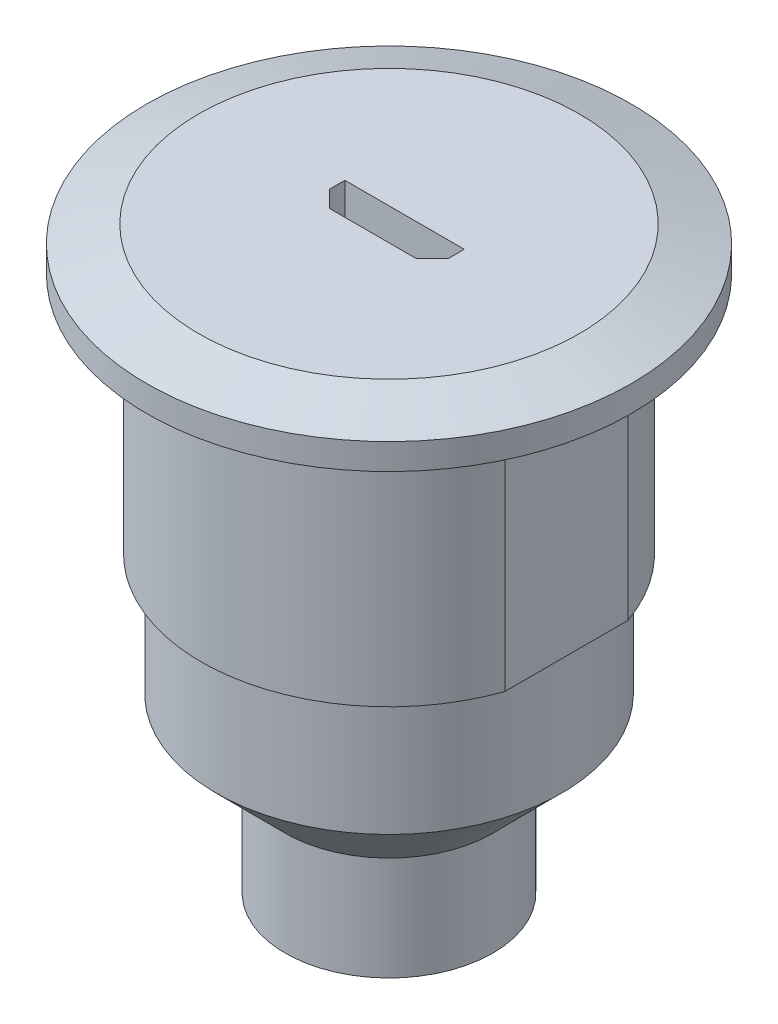
SolidWorks part; units mm, degrees
ref_plane "Plan de face" through (0, 0, 0) normal (0, 0, 1) x (1, 0, 0)
ref_plane "Plan de dessus" through (0, 0, 0) normal (0, 1, 0) x (1, 0, 0)
ref_plane "Plan de droite" through (0, 0, 0) normal (1, 0, 0) x (0, 0, -1)
sketch "Esquisse1" plane through (0, 0, 0) normal (0, 0, 1) x (1, 0, 0)
  line L0 (0, 33.5) -> (0, -37.1703) construction
  line L1 (0, 33.5) -> (-11, 33.5)
  line L2 (-11, 33.5) -> (-14, 32.5)
  line L3 (-14, 32.5) -> (-14, 31)
  line L4 (-14, 31) -> (-10.85, 31)
  line L5 (-10.85, 31) -> (-10.85, 17)
  line L6 (-10.85, 17) -> (-9.985, 17)
  line L7 (-9.985, 17) -> (-9.985, 10)
  line L8 (-9.985, 10) -> (-6, 6)
  line L9 (-6, 6) -> (-6, 0)
  line L10 (-6, 0) -> (0, 0)
  line L11 (0, 33.5) -> (0, 0)
  dimension "D1" = 11
  dimension "D2" = 14
  dimension "D3" = 2.5
  dimension "D4" = 1.5
  dimension "D5" = 14
  dimension "D6" = 7
  dimension "D7" = 31
  dimension "D8" = 6
  dimension "D9" = 6
  dimension "D10" = 10.85
  dimension "D11" = 9.985
revolve "Révolution1" add sketch "Esquisse1" angle 360 about L0
sketch "Esquisse2" plane through (0, 33.5, 0) normal (0, 1, 0) x (1, 0, 0)
  line L0 (-3.45, 0.9) -> (3.45, 0.9)
  line L1 (3.45, 0.9) -> (3.45, 0)
  line L2 (3.45, 0) -> (2.5, -0.95)
  line L3 (2.5, -0.95) -> (-2.5, -0.95)
  line L4 (-2.5, -0.95) -> (-3.45, 0)
  line L5 (-3.45, 0) -> (-3.45, 0.9)
  line L6 (-3.45, 0) -> (-3.45, -0.95) construction
  circle A0 centre (0, 0) radius 11 construction
  circle A1 centre (0, 0) radius 11 construction
  point P3 (0, 0.9)
  dimension "D1" = 6.9
  dimension "D2" = 5
  dimension "D3" = 1.85
extrude "Enlèv. mat.-Extru.1" cut sketch "Esquisse2" against normal blind 5
ref_plane "Plan1" through (0, 0, -10.85) normal (0, 0, -1) x (-1, 0, 0)
sketch "Esquisse3" plane through (0, 0, -10.85) normal (0, 0, -1) x (-1, 0, 0)
  line L0 (-10.85, 17) -> (10.85, 17) construction
  line L1 (10.85, 17) -> (10.25, 17)
  line L2 (10.85, 17) -> (10.85, 31)
  line L3 (10.85, 31) -> (10.25, 31)
  line L4 (10.25, 17) -> (10.25, 31)
  line L5 (-10.25, 17) -> (-10.85, 17)
  line L6 (-10.25, 17) -> (-10.25, 31)
  line L7 (-10.25, 31) -> (-10.85, 31)
  line L8 (-10.85, 17) -> (-10.85, 31)
  line L9 (-10.85, 31) -> (10.85, 31) construction
  line L13 (-10.85, 31) -> (10.85, 31) construction
  dimension "D1" = 20.5
extrude "Enlèv. mat.-Extru.2" cut sketch "Esquisse3" against normal up to next
